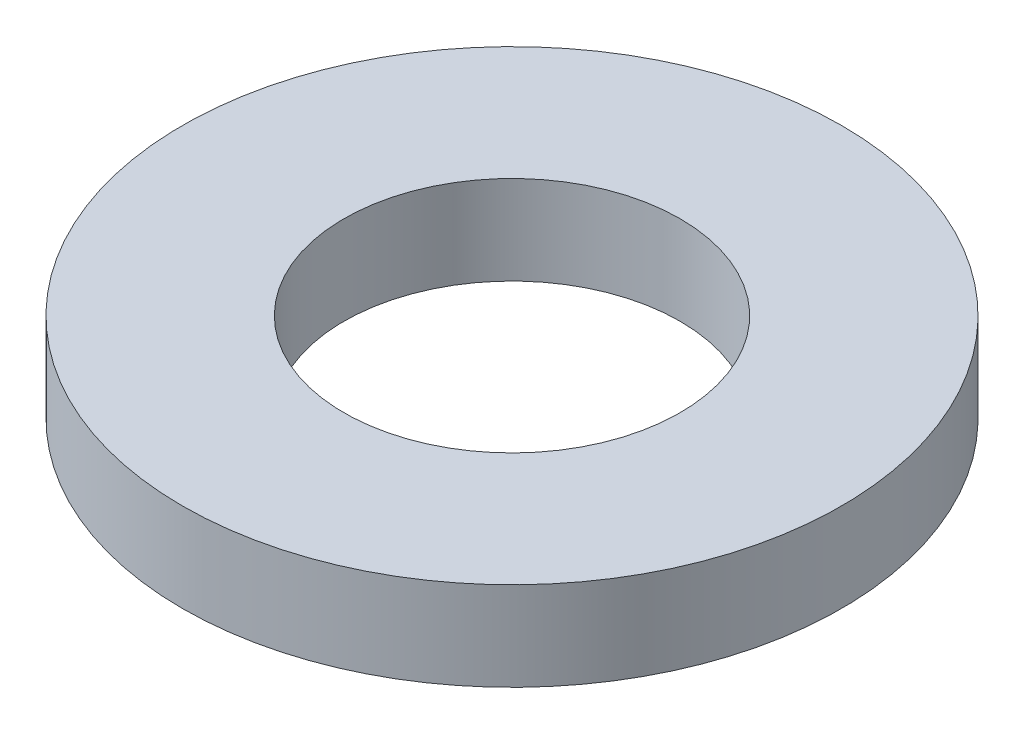
SolidWorks part; units mm, degrees
ref_plane "Front" through (0, 0, 0) normal (0, 0, 1) x (1, 0, 0)
ref_plane "Top" through (0, 0, 0) normal (0, 1, 0) x (1, 0, 0)
ref_plane "Right" through (0, 0, 0) normal (1, 0, 0) x (0, 0, -1)
sketch "Sketch1" plane through (0, 0, 0) normal (0, 0, 1) x (1, 0, 0)
  line L0 (1.778, 0.9398) -> (1.778, 0)
  line L1 (1.778, 0) -> (3.4861, 0)
  line L2 (3.4861, 0) -> (3.4861, 0.9398)
  line L3 (3.4861, 0.9398) -> (1.778, 0.9398)
  line L4 (0, 0.9398) -> (0, 0) construction
revolve "Revolve1" add sketch "Sketch1" angle 360 about L4
